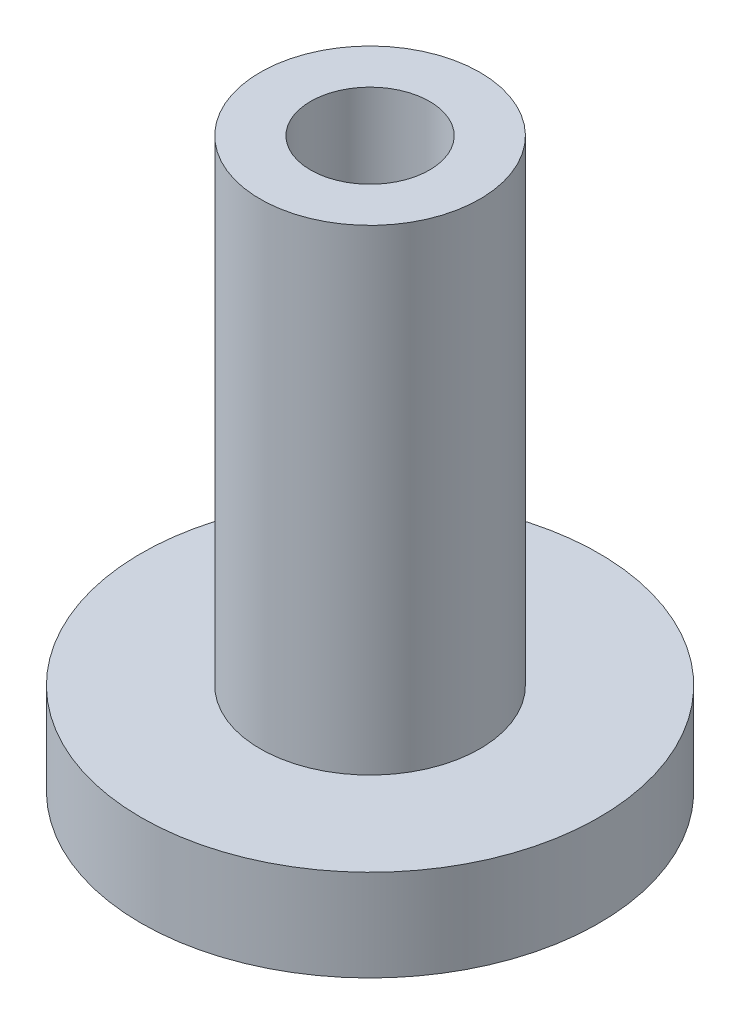
SolidWorks part; units mm, degrees
ref_plane "Front Plane" through (0, 0, 0) normal (0, 0, 1) x (1, 0, 0)
ref_plane "Top Plane" through (0, 0, 0) normal (0, 1, 0) x (1, 0, 0)
ref_plane "Right Plane" through (0, 0, 0) normal (1, 0, 0) x (0, 0, -1)
sketch "Sketch1" plane through (0, 0, 0) normal (0, 1, 0) x (1, 0, 0)
  circle A0 centre (0, 0) radius 6.35
  dimension "D1" = 12.7
extrude "Boss-Extrude1" add sketch "Sketch1" along normal blind 2.54
sketch "Sketch2" plane through (0, 2.54, 0) normal (0, 1, 0) x (1, 0, 0)
  circle A0 centre (0, 0) radius 3.048
  dimension "D1" = 6.096
extrude "Boss-Extrude2" add sketch "Sketch2" along normal blind 13.208
sketch "Sketch3" plane through (0, 15.748, 0) normal (0, 1, 0) x (1, 0, 0)
  circle A0 centre (0, 0) radius 1.651
  dimension "D1" = 3.302
extrude "Cut-Extrude1" cut sketch "Sketch3" against normal through all
sketch "Sketch4" [suppressed] plane through (0, 8.128, 0) normal (0, 1, 0) x (1, 0, 0)
  circle A0 centre (0, 0) radius 1.651
  circle A1 centre (0, 0) radius 3.175
  circle A2 centre (0, 0) radius 3.175
  circle A3 centre (0, 0) radius 1.651 construction
  dimension "D1" = 0
extrude "Boss-Extrude3" [suppressed] add sketch "Sketch4" along normal blind 3.175
